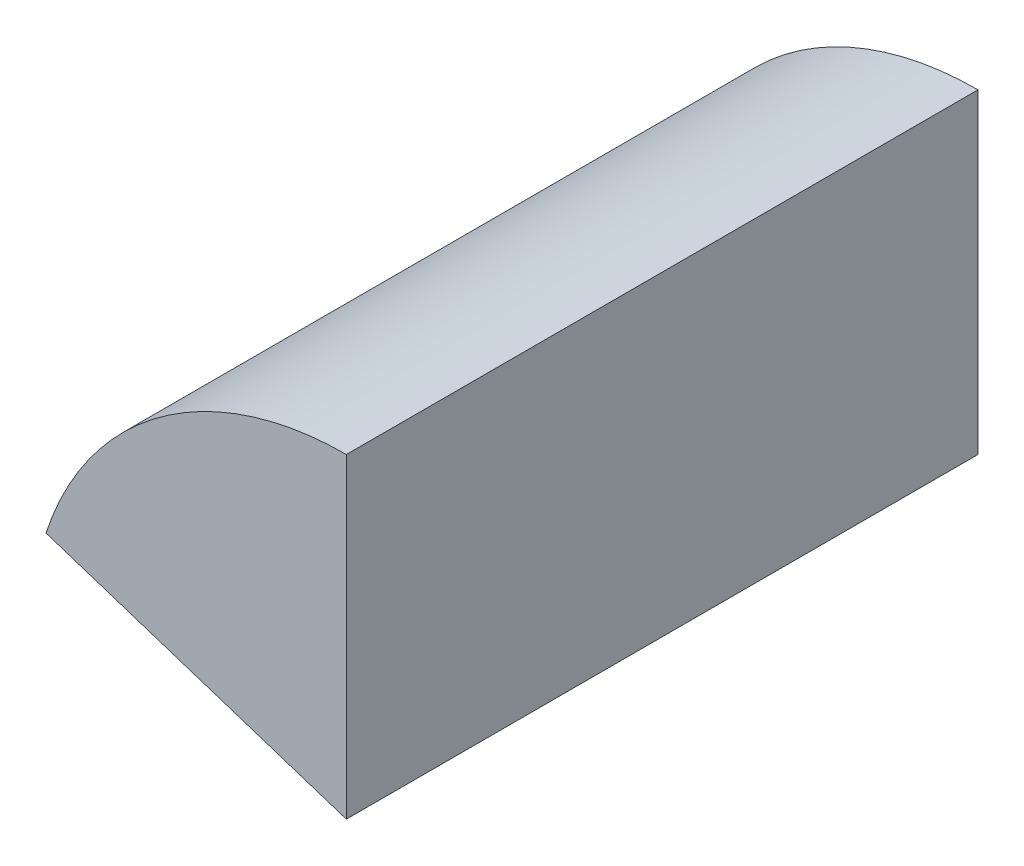
SolidWorks part; units mm, degrees
ref_plane "Alzado" through (0, 0, 0) normal (0, 0, 1) x (1, 0, 0)
ref_plane "Planta" through (0, 0, 0) normal (0, 1, 0) x (1, 0, 0)
ref_plane "Vista lateral" through (0, 0, 0) normal (1, 0, 0) x (0, 0, -1)
sketch "Croquis1" plane through (0, 0, 0) normal (0, 0, 1) x (1, 0, 0)
  line L0 (0, 25) -> (0, 0)
  line L3 (0, 0) -> (-23.7764, 7.7254)
  arc A0 (0, 25) -> (-23.7764, 7.7254) centre (0, 0) ccw
  dimension "D1" = 50
  dimension "D2" = 72
extrude "Saliente-Extruir1" add sketch "Croquis1" along normal blind 50
sketch "Croquis2" plane through (0, 0, 0) normal (0, 0, -1) x (-1, 0, 0)
  circle A0 centre (9.0352, 12.481) radius 5
  dimension "D1" = 10
extrude "Cortar-Extruir1" cut sketch "Croquis2" against normal blind 10 contours A0
